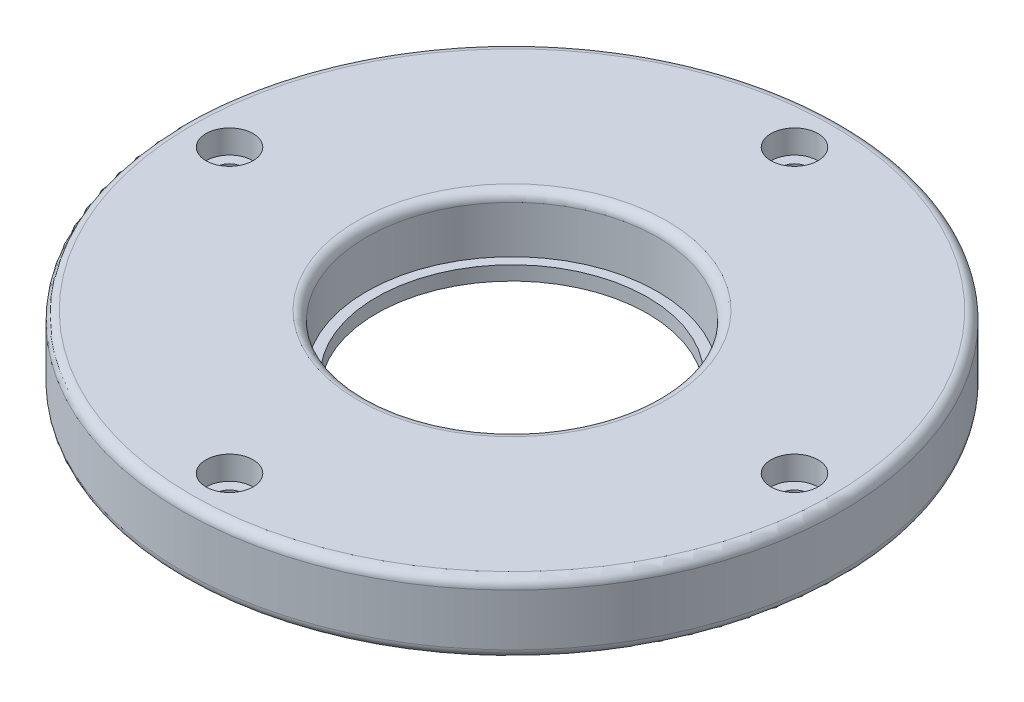
SolidWorks part; units mm, degrees
ref_plane "Front Plane" through (0, 0, 0) normal (0, 0, 1) x (1, 0, 0)
ref_plane "Top Plane" through (0, 0, 0) normal (0, 1, 0) x (1, 0, 0)
ref_plane "Right Plane" through (0, 0, 0) normal (1, 0, 0) x (0, 0, -1)
sketch "Sketch2" plane through (0, 0, 0) normal (0, 1, 0) x (1, 0, 0)
  circle A0 centre (0, 0) radius 70
  dimension "D1" = 140
extrude "Boss-Extrude1" add sketch "Sketch2" along normal blind 15
sketch "Sketch5" plane through (0, 15, 0) normal (0, 1, 0) x (1, 0, 0)
  circle A0 centre (0, 0) radius 30.9
  dimension "D1" = 61.8
extrude "Cut-Extrude1" cut sketch "Sketch5" against normal blind 12
sketch "Sketch6" plane through (0, 3, 0) normal (0, 1, 0) x (1, 0, 0)
  circle A0 centre (0, 0) radius 28.8
  dimension "D1" = 57.6
extrude "Cut-Extrude2" cut sketch "Sketch6" against normal through all
fillet "Fillet1" radius 2 3 edges at (0, 0, 70) (0, 15, 70) (0, 15, 30.9)
hole_wizard "CBORE for M5 SHCS1" positions "Sketch21" profile "Sketch22" counterbore size "M5" standard "ANSI Metric" end condition up to next
sketch "Sketch21" plane through (0, 15, 0) normal (0, 1, 0) x (1, 0, 0)
  line L1 (-60, 0) -> (60, 0) construction
  line L3 (0, 60) -> (0, -60) construction
  point P0 (0, 60)
  point P2 (60, 0)
  point P4 (-60, 0)
  point P6 (0, -60)
  point P19 (0, 0)
  point P21 (0, 0)
  dimension "D1" = 120
  dimension "D2" = 120
sketch "Sketch22" plane through (0, 15, -60) normal (1, 0, 0) x (0, 0, 1)
  line L0 (0, 0) -> (0, 15)
  line L1 (0, 15) -> (2.75, 15)
  line L3 (2.75, 15) -> (2.75, 5)
  line L4 (2.75, 5) -> (5, 5)
  line L5 (5, 5) -> (5, 0)
  line L7 (5, 0) -> (0, 0)
  line L11 (0, -6.35) -> (0, 107.95) construction
  dimension "Thru Hole Dia." = 5.5
  dimension "Thru Hole Depth" = 15
  dimension "C'Bore Dia." = 10
  dimension "C'Bore Depth" = 5
